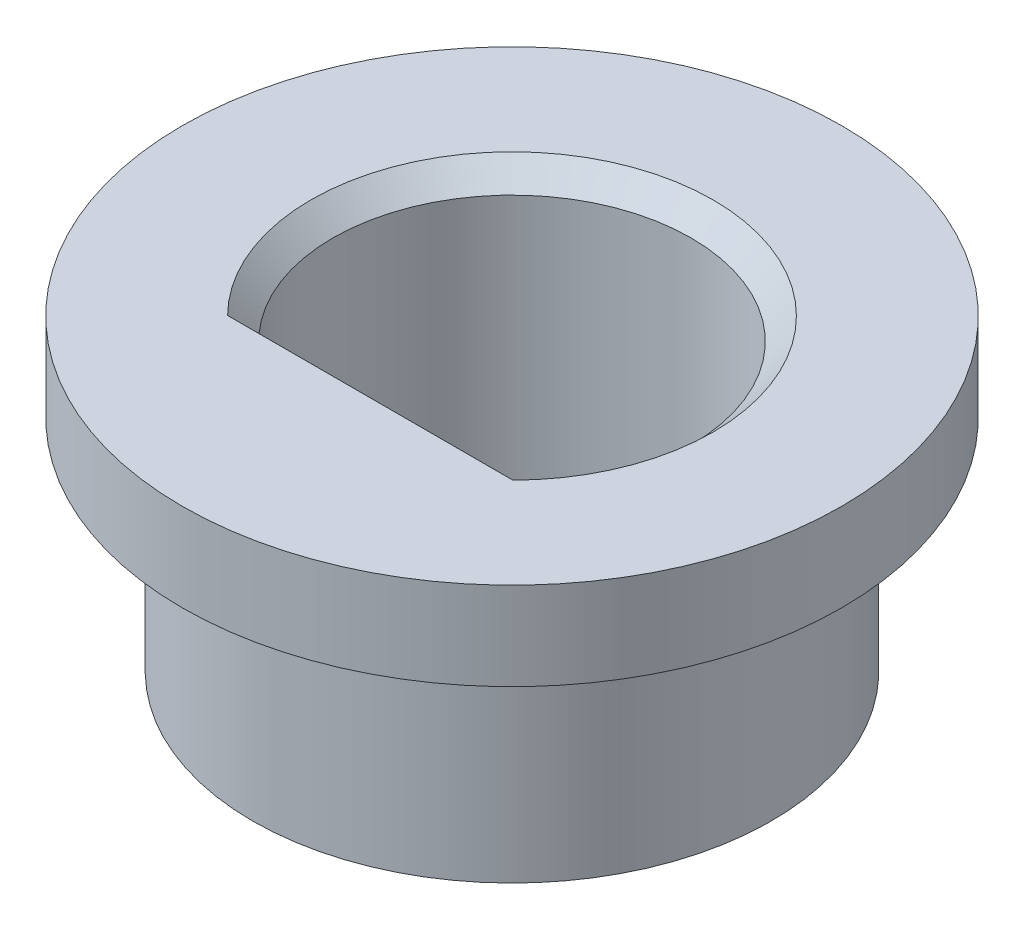
SolidWorks part; units mm, degrees
ref_plane "Ebene vorne" through (0, 0, 0) normal (0, 0, 1) x (1, 0, 0)
ref_plane "Ebene oben" through (0, 0, 0) normal (0, 1, 0) x (1, 0, 0)
ref_plane "Ebene rechts" through (0, 0, 0) normal (1, 0, 0) x (0, 0, -1)
sketch "Skizze1" plane through (0, 0, 0) normal (0, 0, 1) x (1, 0, 0)
  line L0 (0, 0) -> (0, -8283.3421) construction
  line L1 (0, 0) -> (5.9, 0)
  line L2 (5.9, 0) -> (5.9, 5)
  line L3 (5.9, 5) -> (7.5, 5)
  line L4 (7.5, 5) -> (7.5, 7)
  line L5 (7.5, 7) -> (0, 7)
  line L6 (0, 7) -> (0, 0)
  dimension "D1" = 11.8
  dimension "D2" = 15
  dimension "D3" = 5
  dimension "D4" = 7
revolve "Rotation1" add sketch "Skizze1" angle 360 about L0
sketch "Skizze2" plane through (0, 7, 0) normal (0, 1, 0) x (1, 0, 0)
  line L0 (-3.0299, -2.725) -> (3.0299, -2.725)
  arc A0 (3.0299, -2.725) -> (-3.0299, -2.725) centre (0, 0) ccw
  dimension "D1" = 8.15
  dimension "D2" = 6.8
extrude "Schnitt-Linear austragen1" cut sketch "Skizze2" against normal through all
chamfer "Fase1" distance 0.5 angle 45 2 edges at (0, 7, 2.725) (0, 7, -4.075)
